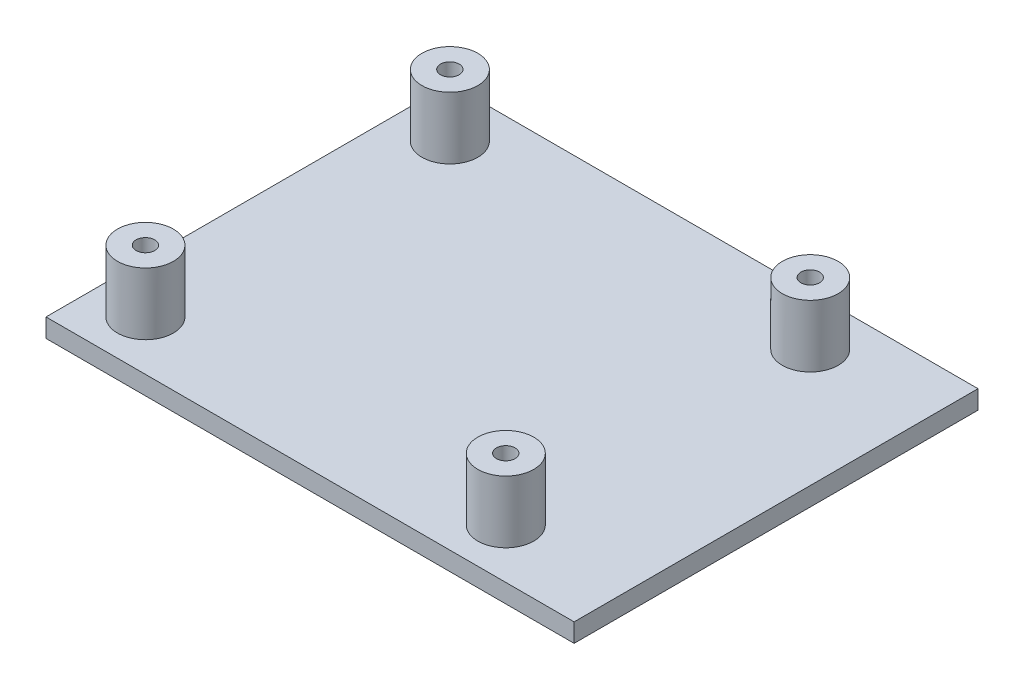
SolidWorks part; units mm, degrees
ref_plane "Front Plane" through (0, 0, 0) normal (0, 0, 1) x (1, 0, 0)
ref_plane "Top Plane" through (0, 0, 0) normal (0, 1, 0) x (1, 0, 0)
ref_plane "Right Plane" through (0, 0, 0) normal (1, 0, 0) x (0, 0, -1)
sketch "Sketch2" plane through (0, 0, 0) normal (0, 1, 0) x (1, 0, 0)
  line L0 (8, 65) -> (8, 57) construction
  line L1 (0, 0) -> (98.2603, 0) construction
  line L2 (0, 0) -> (0, 65) construction
  line L3 (0, 65) -> (98.2603, 65) construction
  line L4 (98.2603, 0) -> (98.2603, 65) construction
  line L5 (8, 57) -> (8, 8) construction
  line L6 (8, 57) -> (66, 57) construction
  line L7 (66, 57) -> (66, 8) construction
  circle A2 centre (66, 8) radius 1.5
  circle A3 centre (66, 8) radius 4.5
  circle A4 centre (66, 57) radius 1.5
  circle A5 centre (66, 57) radius 4.5
  circle A6 centre (8, 57) radius 1.5
  circle A7 centre (8, 57) radius 4.5
  circle A8 centre (8, 8) radius 1.5
  circle A9 centre (8, 8) radius 4.5
  dimension "D7" = 3
  dimension "D8" = 9
  dimension "D1" = 98.2603
  dimension "D2" = 65
  dimension "D3" = 8
  dimension "D4" = 8
  dimension "D5" = 49
  dimension "D6" = 58
extrude "Boss-Extrude1" add sketch "Sketch2" along normal blind 10
sketch "Sketch3" plane through (0, 0, 0) normal (0, 1, 0) x (1, 0, 0)
  line L1 (0, 0) -> (85, 0)
  line L2 (0, 0) -> (0, 65)
  line L3 (0, 65) -> (85, 65)
  line L4 (85, 0) -> (85, 65)
  circle A0 centre (8, 57) radius 4.5 construction
  dimension "D1" = 65
  dimension "D2" = 85
  dimension "D3" = 8
  dimension "D4" = 8
extrude "Boss-Extrude2" add sketch "Sketch3" against normal blind 3
